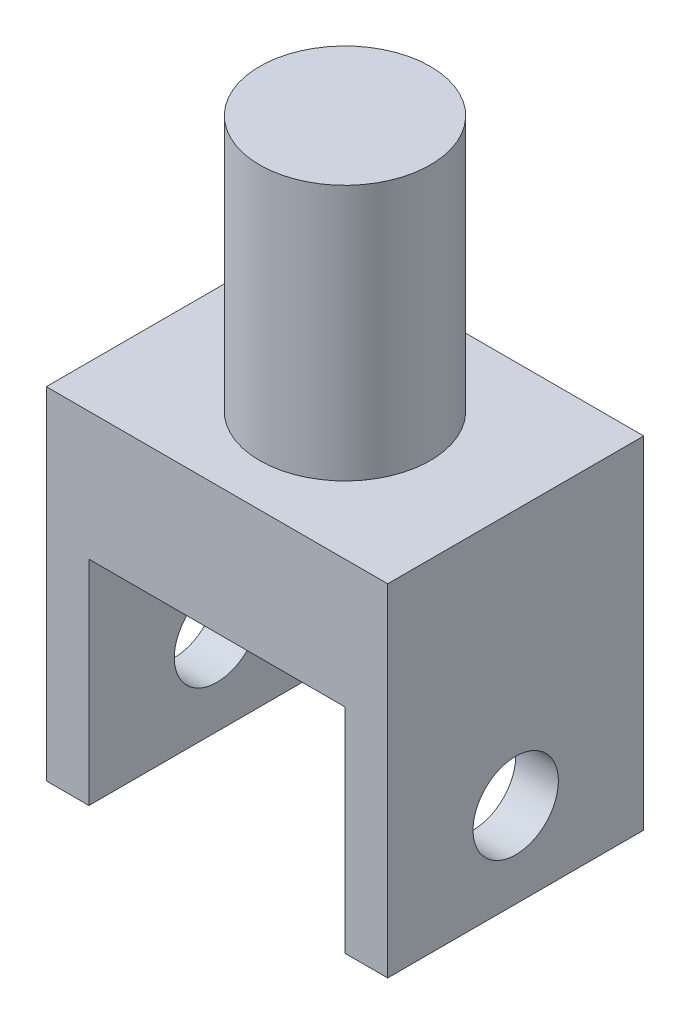
SolidWorks part; units mm, degrees
ref_plane "Front Plane" through (0, 0, 0) normal (0, 0, 1) x (1, 0, 0)
ref_plane "Top Plane" through (0, 0, 0) normal (0, 1, 0) x (1, 0, 0)
ref_plane "Right Plane" through (0, 0, 0) normal (1, 0, 0) x (0, 0, -1)
sketch "Sketch1" plane through (0, 0, 0) normal (0, 1, 0) x (1, 0, 0)
  line L1 (-50.8, -38.1) -> (50.8, -38.1)
  line L2 (-50.8, -38.1) -> (-50.8, 38.1)
  line L3 (-50.8, 38.1) -> (50.8, 38.1)
  line L4 (50.8, -38.1) -> (50.8, 38.1)
  line L5 (-50.8, -38.1) -> (50.8, 38.1) construction
  line L6 (-50.8, 38.1) -> (50.8, -38.1) construction
  point P0 (0, 0)
  dimension "D1" = 101.6
  dimension "D2" = 76.2
extrude "Boss-Extrude1" add sketch "Sketch1" along normal blind 101.6
sketch "Sketch2" plane through (0, 0, 0) normal (0, -1, 0) x (1, 0, 0)
  line L1 (-38.1, -38.1) -> (38.1, -38.1)
  line L2 (-38.1, -38.1) -> (-38.1, 38.1)
  line L3 (-38.1, 38.1) -> (38.1, 38.1)
  line L4 (38.1, -38.1) -> (38.1, 38.1)
  line L5 (-38.1, -38.1) -> (38.1, 38.1) construction
  line L6 (-38.1, 38.1) -> (38.1, -38.1) construction
  line L7 (50.8, 38.1) -> (50.8, -38.1) construction
  point P0 (0, 0)
  dimension "D1" = 76.2
extrude "Cut-Extrude1" cut sketch "Sketch2" against normal blind 63.5
sketch "Sketch3" plane through (50.8, 0, 0) normal (1, 0, 0) x (0, 0, -1)
  line L0 (-38.1, 0) -> (38.1, 0) construction
  circle A0 centre (0, 25.4) radius 12.7
  dimension "D1" = 25.4
  dimension "D2" = 25.4
extrude "Cut-Extrude2" cut sketch "Sketch3" against normal through all contours A0
sketch "Sketch4" plane through (0, 101.6, 0) normal (0, 1, 0) x (1, 0, 0)
  circle A0 centre (0, 0) radius 25.4
  dimension "D1" = 50.8
extrude "Boss-Extrude2" add sketch "Sketch4" along normal blind 76.2
